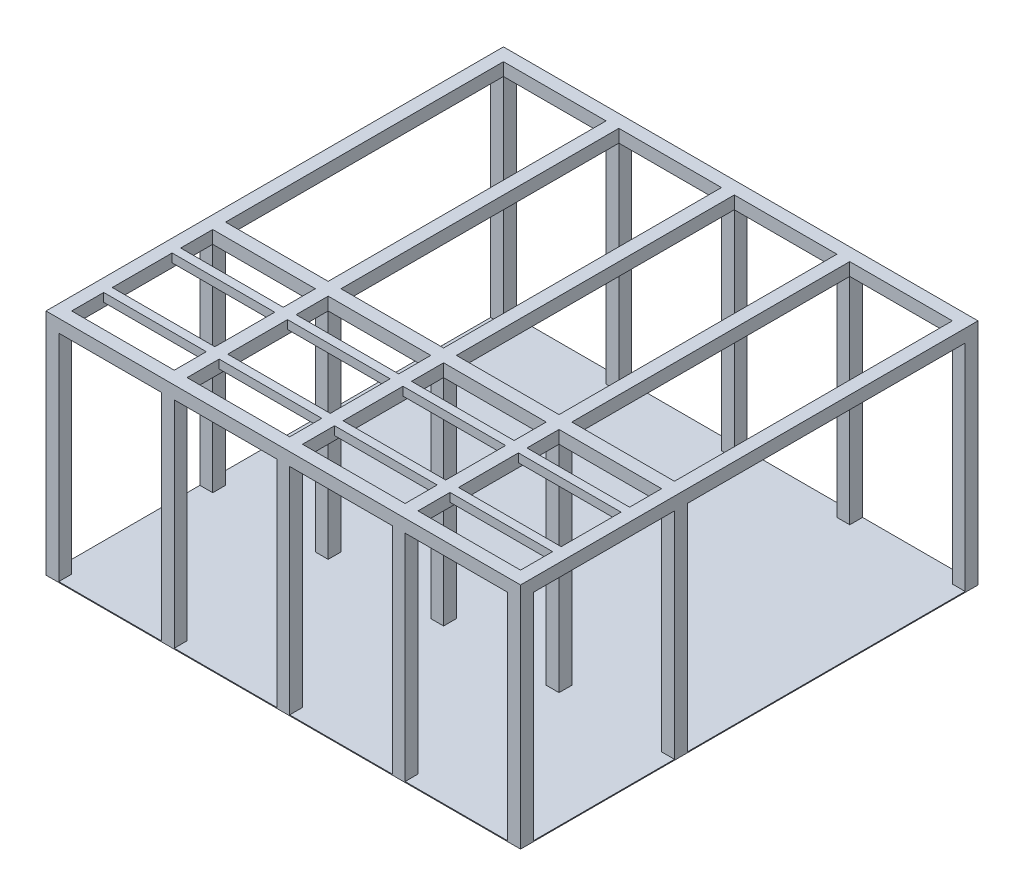
SolidWorks part; units mm, degrees
ref_plane "前视基准面" through (0, 0, 0) normal (0, 0, 1) x (1, 0, 0)
ref_plane "上视基准面" through (0, 0, 0) normal (0, 1, 0) x (1, 0, 0)
ref_plane "右视基准面" through (0, 0, 0) normal (1, 0, 0) x (0, 0, -1)
sketch "草图1" plane through (0, 0, 0) normal (0, 1, 0) x (1, 0, 0)
  line L1 (0, 0) -> (5550, 0)
  line L2 (0, 0) -> (0, 5350)
  line L3 (0, 5350) -> (5550, 5350)
  line L4 (5550, 0) -> (5550, 5350)
  dimension "D1" = 5550
  dimension "D2" = 5350
extrude "凸台-拉伸1" add sketch "草图1" along normal blind 10
sketch "草图2" plane through (0, 10, 0) normal (0, 1, 0) x (1, 0, 0)
  line L1 (0, 0) -> (150, 0)
  line L2 (0, 0) -> (0, 150)
  line L3 (0, 150) -> (150, 150)
  line L4 (150, 0) -> (150, 150)
  dimension "D1" = 150
  dimension "D2" = 150
extrude "凸台-拉伸2" add sketch "草图2" along normal blind 2516
pattern_linear "阵列(线性)1" count 5 spacing 1350 along (1, 0, 0) count 2 spacing 1800 along (0, 0, -1) of "凸台-拉伸2"
sketch "草图3" plane through (0, 10, 0) normal (0, 1, 0) x (1, 0, 0)
  line L1 (0, 5350) -> (150, 5350)
  line L2 (0, 5350) -> (0, 5200)
  line L3 (0, 5200) -> (150, 5200)
  line L4 (150, 5350) -> (150, 5200)
extrude "凸台-拉伸3" add sketch "草图3" along normal blind 2516
pattern_linear "阵列(线性)2" count 5 spacing 1350 along (1, 0, 0) of "凸台-拉伸3"
sketch "草图4" plane through (5550, 0, 0) normal (1, 0, 0) x (0, 0, -1)
  line L1 (150, 2526) -> (0, 2526)
  line L2 (150, 2526) -> (150, 2676)
  line L3 (150, 2676) -> (0, 2676)
  line L4 (0, 2526) -> (0, 2676)
extrude "凸台-拉伸4" add sketch "草图4" against normal up to surface (5550 mm away) up to face at (0, 1371.1667, -2612.5)
pattern_linear "阵列(线性)3" count 2 spacing 1800 along (0, 0, -1) of "凸台-拉伸4"
sketch "草图5" plane through (0, 0, 0) normal (0, 0, 1) x (1, 0, 0)
  line L1 (150, 2526) -> (0, 2526)
  line L2 (150, 2526) -> (150, 2676)
  line L3 (150, 2676) -> (0, 2676)
  line L4 (0, 2526) -> (0, 2676)
extrude "凸台-拉伸5" add sketch "草图5" against normal up to surface (5350 mm away) up to face at (2775, 1267, -5350)
pattern_linear "阵列(线性)4" count 5 spacing 1350 along (1, 0, 0) of "凸台-拉伸5"
pattern_linear "阵列(线性)5" count 2 spacing 5200 along (0, 0, 1) of "凸台-拉伸4"
sketch "草图6" plane through (150, 0, 0) normal (1, 0, 0) x (0, 0, -1)
  line L1 (525, 2576) -> (625, 2576)
  line L2 (525, 2576) -> (525, 2676)
  line L3 (525, 2676) -> (625, 2676)
  line L4 (625, 2576) -> (625, 2676)
  line L5 (1800, 2676) -> (150, 2676) construction
  line L6 (0, 2676) -> (0, 0) construction
  dimension "D1" = 525
extrude "凸台-拉伸6" add sketch "草图6" along normal up to surface (5250 mm away) up to face at (5400, 2601, -975)
pattern_linear "阵列(线性)6" count 2 spacing 800 along (0, 0, -1) of "凸台-拉伸6"
